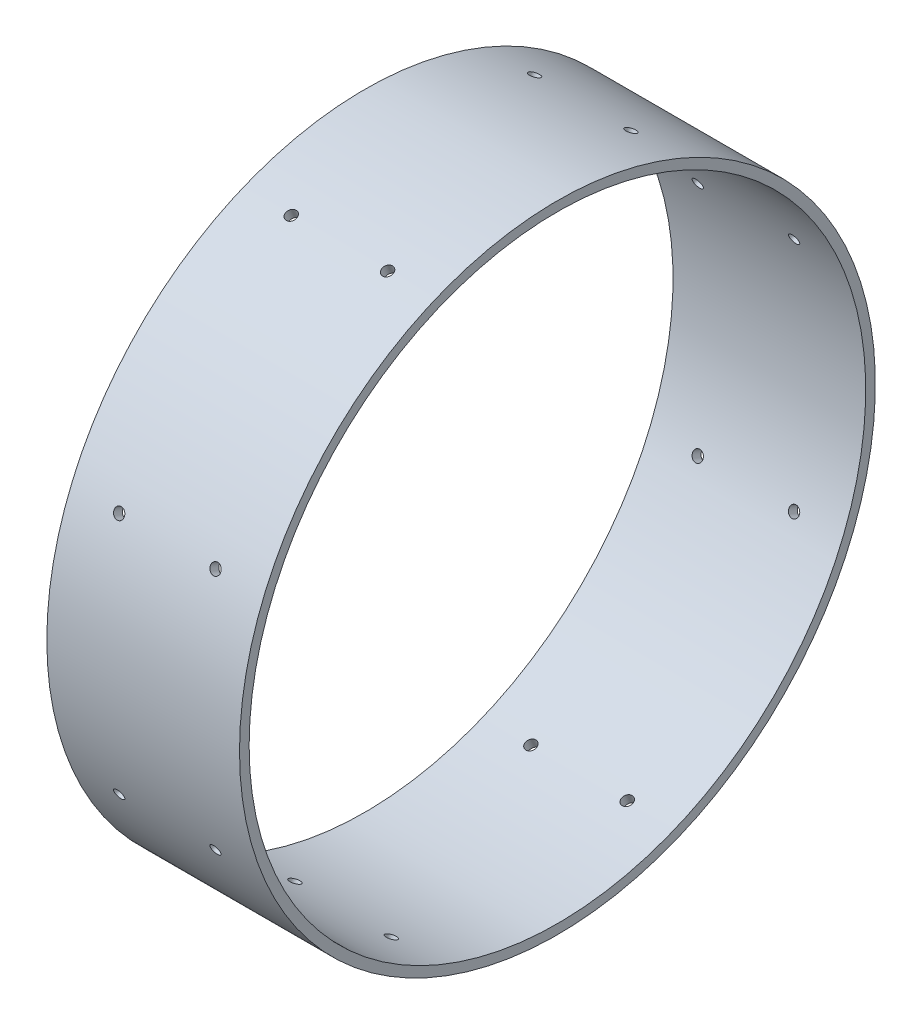
SolidWorks part; units mm, degrees
ref_plane "Front Plane" through (0, 0, 0) normal (0, 0, 1) x (1, 0, 0)
ref_plane "Top Plane" through (0, 0, 0) normal (0, 1, 0) x (1, 0, 0)
ref_plane "Right Plane" through (0, 0, 0) normal (1, 0, 0) x (0, 0, -1)
sketch "Ring Sketch" plane through (0, 0, 0) normal (0, 0, 1) x (1, 0, 0)
  line L0 (-400, 0) -> (400, 0) construction
  line L1 (-30, 96) -> (30, 96)
  line L2 (30, 96) -> (30, 99)
  line L3 (30, 99) -> (-30, 99)
  line L4 (-30, 99) -> (-30, 96)
revolve "Ring" add sketch "Ring Sketch" angle 360 about L0
ref_axis "Engine Axis" through (33, 0, 0) along (-1, 0, 0)
ref_plane "Clock Plane 22.5" through (0, 0, 0) normal (0, -0.9239, -0.3827) x (-1, 0, 0)
sketch "Screw Holes Sketch" plane through (0, 0, 0) normal (0, -0.9239, -0.3827) x (-1, 0, 0)
  circle A0 centre (-15, 0) radius 1.65
  circle A1 centre (15, 0) radius 1.65
extrude "Screw Holes" cut sketch "Screw Holes Sketch" against normal blind 5 from offset 95
pattern_circular "Screw Holes x8" count 8 over 360 about axis through (33, 0, 0) along (-1, 0, 0) of "Screw Holes"
